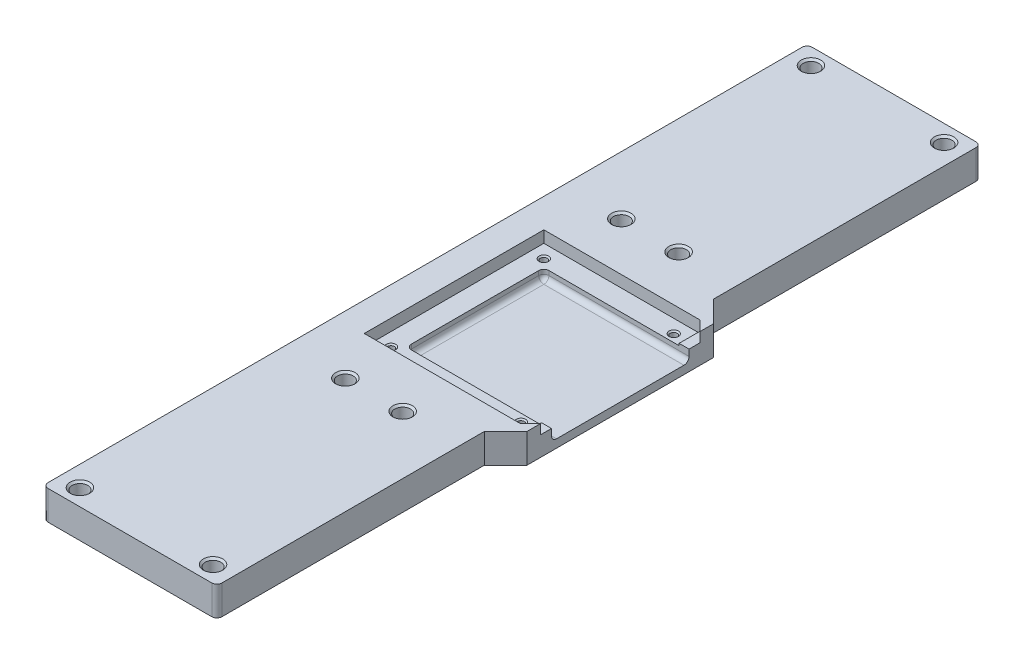
SolidWorks part; units mm, degrees
ref_plane "Front Plane" through (0, 0, 0) normal (0, 0, 1) x (1, 0, 0)
ref_plane "Top Plane" through (0, 0, 0) normal (0, 1, 0) x (1, 0, 0)
ref_plane "Right Plane" through (0, 0, 0) normal (1, 0, 0) x (0, 0, -1)
sketch "Sketch1" plane through (0, 0, 0) normal (0, 1, 0) x (1, 0, 0)
  line L0 (0, -135) -> (0, 135) construction
  line L1 (34.125, 135) -> (-34.125, 135) construction
  line L2 (-34.125, 135) -> (-34.125, -135)
  line L3 (-34.125, 0) -> (34.125, 0) construction
  line L4 (-34.125, 135) -> (-34.125, 148)
  line L5 (-32.125, 150) -> (32.125, 150)
  line L6 (0, 150) -> (0, 135) construction
  line L7 (34.125, 135) -> (34.125, 148)
  line L8 (34.125, 135) -> (34.125, -135)
  line L9 (0, -150) -> (0, -135) construction
  line L10 (34.125, -135) -> (-34.125, -135) construction
  line L11 (34.125, -135) -> (34.125, -148)
  line L12 (-32.125, -150) -> (32.125, -150)
  line L13 (-34.125, -135) -> (-34.125, -148)
  line L14 (-34.125, 138) -> (34.125, 138) construction
  circle A1 centre (-26.125, 143.5) radius 3.075 construction
  circle A2 centre (26.125, 143.5) radius 3.075 construction
  circle A5 centre (26.125, -143.5) radius 3.075 construction
  circle A6 centre (-26.125, -143.5) radius 3.075 construction
  arc A8 (-32.125, -150) -> (-34.125, -148) centre (-32.125, -148) cw
  arc A9 (34.125, -148) -> (32.125, -150) centre (32.125, -148) cw
  arc A10 (34.125, 148) -> (32.125, 150) centre (32.125, 148) ccw
  arc A11 (-34.125, 148) -> (-32.125, 150) centre (-32.125, 148) cw
  circle A12 centre (-11.25, 54.175) radius 3.075 construction
  circle A13 centre (11.25, 54.175) radius 3.075 construction
  circle A14 centre (11.25, -54.175) radius 3.075 construction
  circle A15 centre (-11.25, -54.175) radius 3.075 construction
  point P24 (0, 0)
  point P36 (-34.125, -150)
  point P39 (34.125, -150)
  point P42 (34.125, 150)
  point P45 (-34.125, 150)
  dimension "D5" = 54.175
  dimension "D10" = 2
  dimension "D3" = 6.15
  dimension "D1" = 34.125
  dimension "D2" = 135
  dimension "D4" = 6.5
  dimension "D6" = 8
  dimension "D7" = 8.5
  dimension "D8" = 12
  dimension "D9" = 3
  dimension "D11" = 150
  dimension "D12" = 11.25
extrude "Boss-Extrude1" add sketch "Sketch1" along normal blind 11.5
sketch "Sketch3" plane through (0, 11.5, 0) normal (0, 1, 0) x (1, 0, 0)
  line L0 (0, 0) -> (-34.125, 0) construction
  line L1 (-34.125, 148) -> (-34.125, -148) construction
  line L2 (0, 0) -> (0, 150) construction
  line L3 (32.125, 150) -> (-32.125, 150) construction
  line L4 (3.96, -16.3) -> (3.96, 16.3)
  line L5 (-2.46, -17.8) -> (2.46, -17.8)
  line L6 (-3.96, 16.3) -> (-3.96, -16.3)
  line L7 (2.46, 17.8) -> (-2.46, 17.8)
  line L8 (0, 17.8) -> (0, -17.8) construction
  line L9 (13.25, 0) -> (0, 0) construction
  line L10 (16.15, 10.025) -> (10.35, 10.025)
  line L11 (16.15, 10.025) -> (16.15, -10.025)
  line L12 (16.15, -10.025) -> (10.35, -10.025)
  line L13 (10.35, 10.025) -> (10.35, -10.025)
  line L14 (16.15, 10.025) -> (10.35, -10.025) construction
  line L15 (16.15, -10.025) -> (10.35, 10.025) construction
  line L16 (13.25, 0) -> (13.25, 10.025) construction
  line L17 (-16.15, 10.025) -> (-16.15, -10.025)
  line L18 (-16.15, -10.025) -> (-10.35, -10.025)
  line L23 (-16.15, 10.025) -> (-10.35, 10.025)
  line L24 (-10.35, 10.025) -> (-10.35, -10.025)
  arc A0 (-2.46, 17.8) -> (-3.96, 16.3) centre (-2.46, 16.3) ccw
  arc A1 (3.96, 16.3) -> (2.46, 17.8) centre (2.46, 16.3) ccw
  arc A2 (2.46, -17.8) -> (3.96, -16.3) centre (2.46, -16.3) ccw
  arc A3 (-3.96, -16.3) -> (-2.46, -17.8) centre (-2.46, -16.3) ccw
  point P9 (0, 0)
  point P23 (0, 0)
  dimension "D2" = 1.5
  dimension "D1" = 35.6
  dimension "D3" = 7.92
  dimension "D4" = 20.05
  dimension "D5" = 5.8
  dimension "D6" = 13.25
sketch "Sketch4" plane through (0, 11.5, 0) normal (0, 1, 0) x (1, 0, 0)
  circle A0 centre (-26.125, -143.5) radius 3.075 construction
  circle A1 centre (26.125, -143.5) radius 3.075 construction
  circle A2 centre (26.125, 143.5) radius 3.075 construction
  circle A3 centre (-11.25, -54.175) radius 3.075 construction
  circle A4 centre (11.25, -54.175) radius 3.075 construction
  circle A5 centre (-26.125, 143.5) radius 3.075 construction
  circle A6 centre (11.25, 54.175) radius 3.075 construction
  circle A7 centre (-11.25, 54.175) radius 3.075 construction
  circle A8 centre (-26.125, -143.5) radius 3.075
  circle A9 centre (26.125, -143.5) radius 3.075
  circle A10 centre (26.125, 143.5) radius 3.075
  circle A13 centre (-26.125, 143.5) radius 3.075
  circle A14 centre (-11.25, -54.175) radius 3.075
  circle A15 centre (11.25, -54.175) radius 3.075
  circle A16 centre (11.25, 54.175) radius 3.075
  circle A17 centre (-11.25, 54.175) radius 3.075
extrude "Cut-Extrude1" cut sketch "Sketch4" against normal blind 6
sketch "Sketch27" plane through (0, 11.5, 0) normal (0, 1, 0) x (1, 0, 0)
  line L0 (38.5, 35) -> (-22.5, 35) construction
  line L1 (34.125, 45) -> (42.5, 36.625)
  line L2 (-22.5, 35) -> (-22.5, -35) construction
  line L3 (-22.5, 0) -> (0, 0) construction
  line L4 (38.5, -35) -> (38.5, 35) construction
  line L5 (38.5, -35) -> (-22.5, -35) construction
  line L7 (0, 0) -> (38.5, 0) construction
  line L8 (34.125, -148) -> (34.125, 148) construction
  line L9 (42.5, 36.625) -> (42.5, -36.625)
  line L10 (42.5, 0) -> (38.5, 0) construction
  line L11 (34.125, 45) -> (34.125, -45)
  line L12 (34.125, 0) -> (42.5, 0) construction
  line L13 (34.125, -45) -> (42.5, -36.625)
  circle A0 centre (-17.5, 30) radius 1.6 construction
  circle A1 centre (33.5, 30) radius 1.6 construction
  circle A2 centre (33.5, -30) radius 1.6 construction
  circle A3 centre (-17.5, -30) radius 1.6 construction
  dimension "D8" = 3.2
  dimension "D1" = 22.5
  dimension "D2" = 61
  dimension "D3" = 35
  dimension "D4" = 5
  dimension "D5" = 5
  dimension "D6" = 5
  dimension "D7" = 5
  dimension "D9" = 45
  dimension "D10" = 4
  dimension "D11" = 10
extrude "Boss-Extrude3" add sketch "Sketch27" against normal up to surface (11.5 mm away) up to face at (0, 0, 0)
sketch "Sketch21" plane through (0, 11.5, 0) normal (0, 1, 0) x (1, 0, 0)
  line L0 (38.5, 35) -> (-22.5, 35) construction
  line L1 (38.5, 35) -> (42.5, 31) construction
  line L2 (-22.5, 35) -> (-22.5, -35) construction
  line L3 (-22.5, 0) -> (0, 0) construction
  line L5 (38.5, -35) -> (38.5, 35) construction
  line L6 (38.5, -35) -> (-22.5, -35) construction
  line L7 (42.5, 31) -> (42.5, 31.3536) construction
  line L10 (0, 0) -> (38.5, 0) construction
  line L11 (42.5, 31.3536) -> (42.5, -31.3536)
  line L14 (38.6036, 35.25) -> (42.5, 31.3536)
  line L15 (38.6036, 35.25) -> (-22.75, 35.25)
  line L16 (-22.75, 35.25) -> (-22.75, -35.25)
  line L17 (38.6036, -35.25) -> (-22.75, -35.25)
  line L22 (41.1909, -32.6626) -> (40.4837, -33.8199) construction
  line L23 (42.5, 31.3536) -> (43.8534, 32.707) construction
  line L24 (42.5, -31) -> (40.697, -33.9503) construction
  line L25 (42.5, 31) -> (44.0302, 32.5302) construction
  line L26 (38.6036, -35.25) -> (41.1909, -32.6626) construction
  line L27 (38.5, -35) -> (42.5, -31) construction
  line L29 (42.5, 0) -> (38.5, 0) construction
  line L30 (42.5, -36.625) -> (42.5, 36.625) construction
  line L31 (38.6036, -35.25) -> (42.5, -31.3536)
  circle A0 centre (-17.5, 30) radius 1.6 construction
  circle A1 centre (33.5, 30) radius 1.6 construction
  circle A2 centre (33.5, -30) radius 1.6 construction
  circle A3 centre (-17.5, -30) radius 1.6 construction
  point P2 (-123.1318, 54.1866)
  point P19 (42.5, 0)
  dimension "D8" = 3.2
  dimension "D1" = 22.5
  dimension "D2" = 61
  dimension "D3" = 35
  dimension "D4" = 5
  dimension "D5" = 5
  dimension "D6" = 5
  dimension "D7" = 5
  dimension "D9" = 45
  dimension "D10" = 4
  dimension "D11" = 0.25
extrude "Cut-Extrude6" cut sketch "Sketch21" against normal blind 4.6
sketch "Sketch24" plane through (0, 6.9, 0) normal (0, 1, 0) x (1, 0, 0)
  line L0 (42.5, 27) -> (-14.5, 27)
  line L1 (42.5, -31.3536) -> (42.5, 31.3536) construction
  line L2 (-14.5, 27) -> (-14.5, -27)
  line L3 (-14.5, -27) -> (42.5, -27)
  line L4 (42.5, -27) -> (42.5, 27)
  line L8 (38.5, 35) -> (-22.5, 35) construction
  line L10 (-22.5, 35) -> (-22.5, -35) construction
  line L11 (38.5, -35) -> (-22.5, -35) construction
  point P2 (0, 0)
  point P3 (42.5, -27)
  dimension "D1" = 8
  dimension "D2" = 8
  dimension "D3" = 8
extrude "Cut-Extrude3" cut sketch "Sketch24" against normal blind 3.7 and the other way through all
sketch "Sketch25" plane through (0, 6.9, 0) normal (0, 1, 0) x (1, 0, 0)
  circle A0 centre (33.5, 30) radius 1.35
  circle A1 centre (-17.5, 30) radius 1.35
  circle A2 centre (33.5, -30) radius 1.35
  circle A3 centre (-17.5, -30) radius 1.35
  dimension "D1" = 2.7
extrude "Cut-Extrude4" cut sketch "Sketch25" against normal blind 5
chamfer "Chamfer4" distance 0.5 angle 45 4 edges at (-17.5, 6.9, 31.35) (33.5, 6.9, 31.35) (33.5, 6.9, -28.65) (-17.5, 6.9, -28.65)
fillet "Fillet1" radius 2 5 edges at (14, 3.2, 27) (-14.5, 5.05, 27) (-14.5, 5.05, -27) (-14.5, 3.2, 0) (14, 3.2, -27)
sketch "Sketch26" plane through (0, 6.9, 0) normal (0, 1, 0) x (1, 0, 0)
  line L0 (0, 0) -> (34.125, 0) construction
  line L1 (34.125, -25) -> (34.125, 25) construction
  line L2 (38.6036, 35.25) -> (38.6036, 27)
  line L3 (42.5, 27) -> (-12.5, 27) construction
  line L4 (38.6036, 27) -> (42.5, 27)
  line L5 (42.5, 27) -> (42.5, 31.3536)
  line L7 (42.5, 31.3536) -> (38.6036, 35.25)
  line L8 (42.5, -31.3536) -> (38.6036, -35.25)
  line L11 (38.6036, -27) -> (42.5, -27)
  line L12 (38.6036, -35.25) -> (38.6036, -27)
  line L13 (42.5, 27) -> (42.5, 31.3536) construction
  line L14 (42.5, -31.3536) -> (42.5, -27)
extrude "Boss-Extrude2" add sketch "Sketch26" along normal blind 0.8
chamfer "Chamfer5" distance 0.75 angle 45 8 edges at (-26.125, 11.5, 146.575) (26.125, 11.5, 146.575) (26.125, 11.5, -140.425) (-26.125, 11.5, -140.425) (-11.25, 11.5, 57.25) (11.25, 11.5, 57.25) (11.25, 11.5, -51.1) (-11.25, 11.5, -51.1)
equation "\"D5@Sketch21\"=\"D4@Sketch21\""
equation "\"D6@Sketch21\"=\"D4@Sketch21\""
equation "\"D7@Sketch21\"=\"D4@Sketch21\""
equation "\"D2@Sketch24\"=\"D1@Sketch24\""
equation "\"D3@Sketch24\"=\"D1@Sketch24\""
